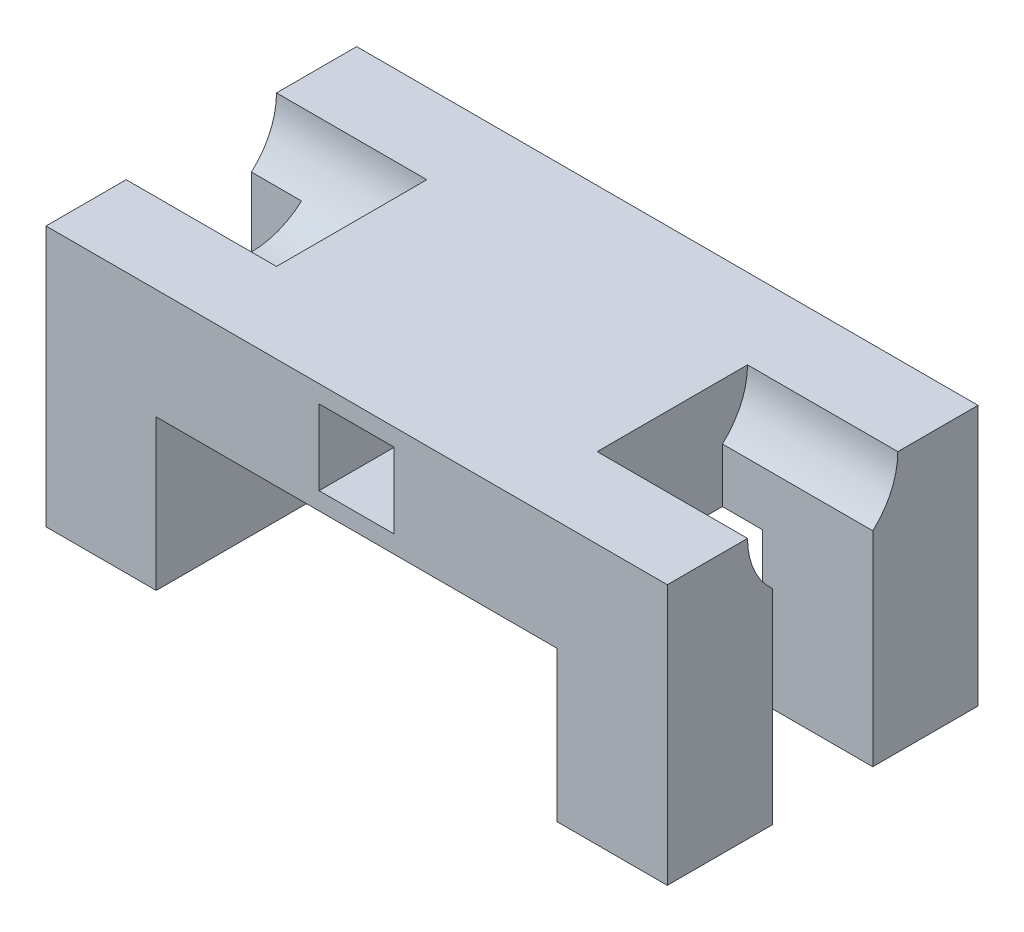
SolidWorks part; units mm, degrees
material "Ductile Iron"
ref_plane "Front Plane" through (0, 0, 0) normal (0, 0, 1) x (1, 0, 0)
ref_plane "Top Plane" through (0, 0, 0) normal (0, 1, 0) x (1, 0, 0)
ref_plane "Right Plane" through (0, 0, 0) normal (1, 0, 0) x (0, 0, -1)
sketch "Sketch1" plane through (0, 0, 0) normal (0, 0, 1) x (1, 0, 0)
  line L36 (0, 0) -> (0, 52)
  line L37 (0, 52) -> (124, 52)
  line L38 (124, 52) -> (124, 0.0298)
  line L39 (124, 0.0298) -> (102, 0.0298)
  line L40 (102, 0.0298) -> (102, 30)
  line L41 (102, 30) -> (22, 30)
  line L42 (22, 30) -> (22, 0)
  line L43 (22, 0) -> (0, 0)
  line L45 (69.5, 48.5) -> (54.5, 48.5)
  line L46 (69.5, 48.5) -> (69.5, 33.5)
  line L47 (69.5, 33.5) -> (54.5, 33.5)
  line L48 (54.5, 48.5) -> (54.5, 33.5)
  line L49 (69.5, 48.5) -> (54.5, 33.5) construction
  line L50 (69.5, 33.5) -> (54.5, 48.5) construction
  point P12 (62, 41)
  dimension "D1" = 30
  dimension "D2" = 124
  dimension "D3" = 52
  dimension "D4" = 80
  dimension "D5" = 15
  dimension "D6" = 15
  dimension "D7" = 62
  dimension "D8" = 11
extrude "Boss-Extrude2" add sketch "Sketch1" along normal blind 62
sketch "Sketch2" plane through (0, 0, 0) normal (-1, 0, 0) x (0, 0, 1)
  line L0 (62, 0) -> (0, 0) construction
  line L1 (21, 0) -> (41, 0)
  line L2 (21, 0) -> (21, 52)
  line L3 (21, 52) -> (41, 52)
  line L4 (41, 0) -> (41, 52)
  line L5 (21, 0) -> (41, 52) construction
  line L6 (21, 52) -> (41, 0) construction
  line L7 (62, 52) -> (0, 52) construction
  line L8 (0, 52) -> (0, 0) construction
  point P4 (31, 26)
  point P9 (0, 0)
  dimension "D1" = 20
  dimension "D2" = 31
extrude "Cut-Extrude1" cut sketch "Sketch2" against normal blind 10
sketch "Sketch3" plane through (0, 0, 0) normal (-1, 0, 0) x (0, 0, 1)
  line L0 (21, 52) -> (0, 52) construction
  line L1 (62, 52) -> (41, 52) construction
  line L2 (62, 52) -> (62, 0) construction
  line L4 (41, 52) -> (21, 52) construction
  line L5 (16, 52) -> (46, 52)
  arc A0 (16, 52) -> (46, 52) centre (31, 52) ccw
  dimension "D1" = 15
  dimension "D2" = 31
extrude "Cut-Extrude2" cut sketch "Sketch3" against normal blind 30
sketch3d "3DSketch1"
  line L4 (0, 0, 41) -> (0, 0, 21)
  line L5 (0, 52, 41) -> (0, 0, 41)
  line L6 (0, 52, 21) -> (0, 52, 41)
  line L7 (0, 0, 21) -> (0, 52, 21)
  line L8 (0, 0, 41) -> (0, 0, 21)
  line L9 (0, 52, 41) -> (0, 0, 41)
  line L10 (0, 52, 21) -> (0, 52, 41)
  line L11 (0, 0, 21) -> (0, 52, 21)
  dimension "D1" = 0
sketch "Sketch5" plane through (124, 0, 0) normal (1, 0, 0) x (0, 0, -1)
  line L1 (-21, 52) -> (-41, 52)
  line L2 (-21, 52) -> (-21, 0)
  line L3 (-21, 0) -> (-41, 0)
  line L4 (-41, 52) -> (-41, 0)
  line L5 (-21, 52) -> (-41, 0) construction
  line L6 (-21, 0) -> (-41, 52) construction
  point P4 (-31, 26)
extrude "Cut-Extrude4" cut sketch "Sketch5" against normal blind 30
sketch "Sketch6" plane through (124, 0, 0) normal (1, 0, 0) x (0, 0, -1)
  line L0 (-62, 52) -> (-41, 52) construction
  line L1 (-21, 52) -> (-41, 52) construction
  line L2 (-46, 52) -> (-16, 52)
  arc A0 (-46, 52) -> (-16, 52) centre (-31, 52) ccw
  dimension "D1" = 15
extrude "Cut-Extrude5" cut sketch "Sketch6" against normal blind 30
